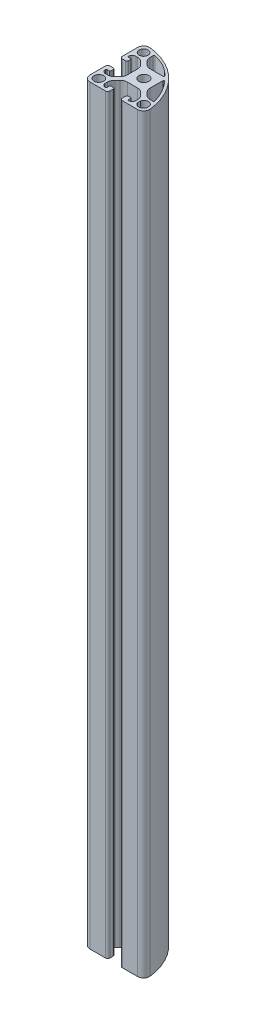
SolidWorks part; units mm, degrees
ref_plane "Alzado" through (0, 0, 0) normal (0, 0, 1) x (1, 0, 0)
ref_plane "Planta" through (0, 0, 0) normal (0, 1, 0) x (1, 0, 0)
ref_plane "Vista lateral" through (0, 0, 0) normal (1, 0, 0) x (0, 0, -1)
sketch "Croquis1" plane through (0, 0, 0) normal (0, 1, 0) x (1, 0, 0)
  line L0 (-18.2, 12.3) -> (-18.2, 15.7771)
  line L1 (-12.3, 11.8) -> (-17.7, 11.8)
  line L2 (-11.8, 16.9053) -> (-11.8, 12.3)
  line L3 (11.8, -17.7) -> (11.8, -12.3)
  line L4 (15.7771, -18.2) -> (12.3, -18.2)
  line L5 (12.3, -11.8) -> (16.9053, -11.8)
  line L6 (-18.2, -16) -> (-18.2, -12.3)
  line L7 (-12.3, -18.2) -> (-16, -18.2)
  line L8 (-11.8, -12.3) -> (-11.8, -17.7)
  line L9 (-17.7, -11.8) -> (-12.3, -11.8)
  line L10 (-10.1, 14.2924) -> (-10.1, 16.2371)
  line L11 (-6.9431, 9.0645) -> (-8.6355, 10.7569)
  line L12 (5.1332, 7.6) -> (-3.4076, 7.6)
  line L13 (4.1, -16.35) -> (4.1, -18.5)
  line L14 (5.6, -20) -> (15.7771, -20)
  line L15 (-20, 15.7771) -> (-20, 5.6)
  line L16 (-18.5, 4.1) -> (-16.35, 4.1)
  line L17 (-15.35, 5.1) -> (-15.35, 6.6)
  line L18 (-15.85, 7.1) -> (-17.5, 7.1)
  line L19 (-15.5, 10.1) -> (-14.2924, 10.1)
  line L20 (-10.7569, 8.6355) -> (-9.0645, 6.9431)
  line L21 (-7.6, 3.4076) -> (-7.6, -3.4076)
  line L22 (-9.0645, -6.9431) -> (-10.7569, -8.6355)
  line L23 (-14.2924, -10.1) -> (-15.5, -10.1)
  line L24 (-17.5, -7.1) -> (-15.85, -7.1)
  line L25 (-15.35, -6.6) -> (-15.35, -5.1)
  line L26 (-16.35, -4.1) -> (-18.5, -4.1)
  line L27 (-20, -5.6) -> (-20, -16)
  line L28 (-16, -20) -> (-5.6, -20)
  line L29 (-4.1, -18.5) -> (-4.1, -16.35)
  line L30 (-5.1, -15.35) -> (-6.6, -15.35)
  line L31 (-7.1, -15.85) -> (-7.1, -17.5)
  line L32 (-10.1, -15.5) -> (-10.1, -14.2924)
  line L33 (-8.6355, -10.7569) -> (-6.9431, -9.0645)
  line L34 (-3.4076, -7.6) -> (3.4076, -7.6)
  line L35 (6.9431, -9.0645) -> (8.6355, -10.7569)
  line L36 (10.1, -14.2924) -> (10.1, -15.5)
  line L37 (7.1, -17.5) -> (7.1, -15.85)
  line L38 (6.6, -15.35) -> (5.1, -15.35)
  line L39 (16.2371, -10.1) -> (14.2924, -10.1)
  line L40 (10.7569, -8.6355) -> (9.0645, -6.9431)
  line L41 (7.6, -3.4076) -> (7.6, 5.1332)
  circle A0 centre (0, 0) radius 3.35
  arc A1 (-15.7556, 17.9635) -> (-18.2, 15.7771) centre (-16, 15.7771) ccw
  arc A2 (-18.2, 12.3) -> (-17.7, 11.8) centre (-17.7, 12.3) ccw
  arc A3 (-12.3, 11.8) -> (-11.8, 12.3) centre (-12.3, 12.3) ccw
  arc A4 (-11.8, 16.9053) -> (-12.1979, 17.3947) centre (-12.3, 16.9053) ccw
  arc A5 (-12.1979, 17.3947) -> (-15.7556, 17.9635) centre (-20, -20) ccw
  arc A6 (12.3, -11.8) -> (11.8, -12.3) centre (12.3, -12.3) ccw
  arc A7 (11.8, -17.7) -> (12.3, -18.2) centre (12.3, -17.7) ccw
  arc A8 (15.7771, -18.2) -> (17.9635, -15.7556) centre (15.7771, -16) ccw
  arc A9 (17.9635, -15.7556) -> (17.3947, -12.1979) centre (-20, -20) ccw
  arc A10 (17.3947, -12.1979) -> (16.9053, -11.8) centre (16.9053, -12.3) ccw
  arc A11 (-17.7, -11.8) -> (-18.2, -12.3) centre (-17.7, -12.3) ccw
  arc A12 (-18.2, -16) -> (-16, -18.2) centre (-16, -16) ccw
  arc A13 (-12.3, -18.2) -> (-11.8, -17.7) centre (-12.3, -17.7) ccw
  arc A14 (-11.8, -12.3) -> (-12.3, -11.8) centre (-12.3, -12.3) ccw
  arc A15 (4.1, -18.5) -> (5.6, -20) centre (5.6, -18.5) ccw
  arc A16 (15.7771, -20) -> (19.7523, -15.5556) centre (15.7771, -16) ccw
  arc A17 (19.7523, -15.5556) -> (-15.5556, 19.7523) centre (-20, -20) ccw
  arc A18 (-15.5556, 19.7523) -> (-20, 15.7771) centre (-16, 15.7771) ccw
  arc A19 (-20, 5.6) -> (-18.5, 4.1) centre (-18.5, 5.6) ccw
  arc A20 (-16.35, 4.1) -> (-15.35, 5.1) centre (-16.35, 5.1) ccw
  arc A21 (-15.35, 6.6) -> (-15.85, 7.1) centre (-15.85, 6.6) ccw
  arc A22 (-18, 7.6) -> (-17.5, 7.1) centre (-17.5, 7.6) ccw
  arc A23 (-15.5, 10.1) -> (-18, 7.6) centre (-15.5, 7.6) ccw
  arc A24 (-10.7569, 8.6355) -> (-14.2924, 10.1) centre (-14.2924, 5.1) ccw
  arc A25 (-7.6, 3.4076) -> (-9.0645, 6.9431) centre (-12.6, 3.4076) ccw
  arc A26 (-9.0645, -6.9431) -> (-7.6, -3.4076) centre (-12.6, -3.4076) ccw
  arc A27 (-14.2924, -10.1) -> (-10.7569, -8.6355) centre (-14.2924, -5.1) ccw
  arc A28 (-18, -7.6) -> (-15.5, -10.1) centre (-15.5, -7.6) ccw
  arc A29 (-17.5, -7.1) -> (-18, -7.6) centre (-17.5, -7.6) ccw
  arc A30 (-15.85, -7.1) -> (-15.35, -6.6) centre (-15.85, -6.6) ccw
  arc A31 (-15.35, -5.1) -> (-16.35, -4.1) centre (-16.35, -5.1) ccw
  arc A32 (-18.5, -4.1) -> (-20, -5.6) centre (-18.5, -5.6) ccw
  arc A33 (-20, -16) -> (-16, -20) centre (-16, -16) ccw
  arc A34 (-5.6, -20) -> (-4.1, -18.5) centre (-5.6, -18.5) ccw
  arc A35 (-4.1, -16.35) -> (-5.1, -15.35) centre (-5.1, -16.35) ccw
  arc A36 (-6.6, -15.35) -> (-7.1, -15.85) centre (-6.6, -15.85) ccw
  arc A37 (-7.6, -18) -> (-7.1, -17.5) centre (-7.6, -17.5) ccw
  arc A38 (-10.1, -15.5) -> (-7.6, -18) centre (-7.6, -15.5) ccw
  arc A39 (-8.6355, -10.7569) -> (-10.1, -14.2924) centre (-5.1, -14.2924) ccw
  arc A40 (-3.4076, -7.6) -> (-6.9431, -9.0645) centre (-3.4076, -12.6) ccw
  arc A41 (6.9431, -9.0645) -> (3.4076, -7.6) centre (3.4076, -12.6) ccw
  arc A42 (10.1, -14.2924) -> (8.6355, -10.7569) centre (5.1, -14.2924) ccw
  arc A43 (7.6, -18) -> (10.1, -15.5) centre (7.6, -15.5) ccw
  arc A44 (7.1, -17.5) -> (7.6, -18) centre (7.6, -17.5) ccw
  arc A45 (7.1, -15.85) -> (6.6, -15.35) centre (6.6, -15.85) ccw
  arc A46 (5.1, -15.35) -> (4.1, -16.35) centre (5.1, -16.35) ccw
  arc A47 (-9.4621, 16.7177) -> (-10.1, 16.2371) centre (-9.6, 16.2371) ccw
  arc A48 (-10.1, 14.2924) -> (-8.6355, 10.7569) centre (-5.1, 14.2924) ccw
  arc A49 (-6.9431, 9.0645) -> (-3.4076, 7.6) centre (-3.4076, 12.6) ccw
  arc A50 (5.1332, 7.6) -> (5.4666, 8.4727) centre (5.1332, 8.1) ccw
  arc A51 (16.7177, -9.4621) -> (8.4727, 5.4666) centre (-20, -20) ccw
  arc A52 (16.2371, -10.1) -> (16.7177, -9.4621) centre (16.2371, -9.6) ccw
  arc A53 (10.7569, -8.6355) -> (14.2924, -10.1) centre (14.2924, -5.1) ccw
  arc A54 (7.6, -3.4076) -> (9.0645, -6.9431) centre (12.6, -3.4076) ccw
  arc A55 (8.4727, 5.4666) -> (7.6, 5.1332) centre (8.1, 5.1332) ccw
  arc A56 (-9.4621, 16.7177) -> (5.4666, 8.4727) centre (-14.5044, -10.0495) cw
extrude "Saliente-Extruir1" add sketch "Croquis1" along normal blind 500
sketch "Croquis2" plane through (0, 500, 0) normal (0, 1, 0) x (1, 0, 0)
  line L0 (-18.2, 15.7771) -> (-18.2, 12.3) construction
  line L1 (-17.7, 11.8) -> (-12.3, 11.8) construction
  line L2 (-11.8, 12.3) -> (-11.8, 16.9053) construction
  line L3 (-18.2, 15.7771) -> (-18.2, 12.3)
  line L4 (-17.7, 11.8) -> (-12.3, 11.8)
  line L5 (-11.8, 12.3) -> (-11.8, 16.9053)
  line L6 (-16, -18.2) -> (-12.3, -18.2) construction
  line L7 (-18.2, -12.3) -> (-18.2, -16) construction
  line L8 (-12.3, -11.8) -> (-17.7, -11.8) construction
  line L9 (-11.8, -17.7) -> (-11.8, -12.3) construction
  line L10 (-16, -18.2) -> (-12.3, -18.2)
  line L11 (-18.2, -12.3) -> (-18.2, -16)
  line L12 (-12.3, -11.8) -> (-17.7, -11.8)
  line L13 (-11.8, -17.7) -> (-11.8, -12.3)
  line L14 (12.3, -18.2) -> (15.7771, -18.2) construction
  line L15 (11.8, -12.3) -> (11.8, -17.7) construction
  line L16 (16.9053, -11.8) -> (12.3, -11.8) construction
  line L17 (12.3, -18.2) -> (15.7771, -18.2)
  line L18 (11.8, -12.3) -> (11.8, -13.9666)
  line L19 (16.9053, -11.8) -> (12.3, -11.8)
  line L20 (11.8, -16.0334) -> (11.8, -17.7)
  arc A0 (-11.8, 16.9053) -> (-12.1979, 17.3947) centre (-12.3, 16.9053) ccw construction
  arc A1 (-12.1979, 17.3947) -> (-15.7556, 17.9635) centre (-20, -20) ccw construction
  arc A2 (-15.7556, 17.9635) -> (-18.2, 15.7771) centre (-16, 15.7771) ccw construction
  arc A3 (-18.2, 12.3) -> (-17.7, 11.8) centre (-17.7, 12.3) ccw construction
  arc A4 (-12.3, 11.8) -> (-11.8, 12.3) centre (-12.3, 12.3) ccw construction
  arc A5 (-11.8, 16.9053) -> (-12.1979, 17.3947) centre (-12.3, 16.9053) ccw
  arc A6 (-12.1979, 17.3947) -> (-15.7556, 17.9635) centre (-20, -20) ccw
  arc A7 (-15.7556, 17.9635) -> (-18.2, 15.7771) centre (-16, 15.7771) ccw
  arc A8 (-18.2, 12.3) -> (-17.7, 11.8) centre (-17.7, 12.3) ccw
  arc A9 (-12.3, 11.8) -> (-11.8, 12.3) centre (-12.3, 12.3) ccw
  arc A10 (-12.3, -18.2) -> (-11.8, -17.7) centre (-12.3, -17.7) ccw construction
  arc A11 (-18.2, -16) -> (-16, -18.2) centre (-16, -16) ccw construction
  arc A12 (-17.7, -11.8) -> (-18.2, -12.3) centre (-17.7, -12.3) ccw construction
  arc A13 (-11.8, -12.3) -> (-12.3, -11.8) centre (-12.3, -12.3) ccw construction
  arc A14 (-12.3, -18.2) -> (-11.8, -17.7) centre (-12.3, -17.7) ccw
  arc A15 (-18.2, -16) -> (-16, -18.2) centre (-16, -16) ccw
  arc A16 (-17.7, -11.8) -> (-18.2, -12.3) centre (-17.7, -12.3) ccw
  arc A17 (-11.8, -12.3) -> (-12.3, -11.8) centre (-12.3, -12.3) ccw
  arc A18 (17.3947, -12.1979) -> (16.9053, -11.8) centre (16.9053, -12.3) ccw construction
  arc A19 (17.9635, -15.7556) -> (17.3947, -12.1979) centre (-20, -20) ccw construction
  arc A20 (15.7771, -18.2) -> (17.9635, -15.7556) centre (15.7771, -16) ccw construction
  arc A21 (11.8, -17.7) -> (12.3, -18.2) centre (12.3, -17.7) ccw construction
  arc A22 (12.3, -11.8) -> (11.8, -12.3) centre (12.3, -12.3) ccw construction
  arc A23 (17.3947, -12.1979) -> (16.9053, -11.8) centre (16.9053, -12.3) ccw
  arc A24 (17.9635, -15.7556) -> (17.9551, -15.6816) centre (-20, -20) ccw
  arc A25 (15.7771, -18.2) -> (17.9635, -15.7556) centre (15.7771, -16) ccw
  arc A26 (11.8, -17.7) -> (12.3, -18.2) centre (12.3, -17.7) ccw
  arc A27 (12.3, -11.8) -> (11.8, -12.3) centre (12.3, -12.3) ccw
  circle A28 centre (-14.9928, 14.8209) radius 3.0209
  circle A29 centre (-15, -15) radius 3.2
  circle A30 centre (14.8285, -15) radius 3.2
  arc A31 (17.6371, -13.4664) -> (17.3947, -12.1979) centre (-20, -20) ccw
extrude "Saliente-Extruir2" add sketch "Croquis2" against normal up to surface (500 mm away) contours A29 L13 A17 L12 | A29 L10 A14 L13 | A29 L11 A15 L10 | A29 L12 A16 L11 | A28 A6 A7 L3 A8 L4 | A28 L4 A9 L5 A5 A6 | A30 A31 A23 L19 | A30 L19 A27 L18 | A30 L20 A26 L17 | A30 L17 A25 A24 up to face at (-4.7129, 0, -11.4358)
